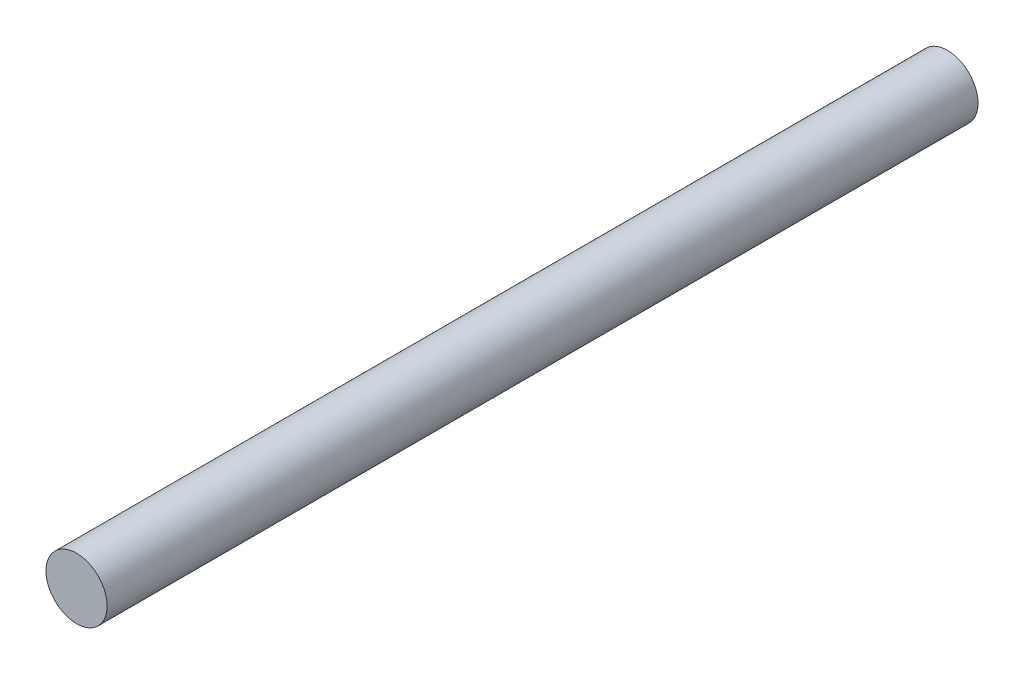
SolidWorks part; units mm, degrees
ref_plane "Front Plane" through (0, 0, 0) normal (0, 0, 1) x (1, 0, 0)
ref_plane "Top Plane" through (0, 0, 0) normal (0, 1, 0) x (1, 0, 0)
ref_plane "Right Plane" through (0, 0, 0) normal (1, 0, 0) x (0, 0, -1)
sketch "Sketch1" plane through (0, 0, 0) normal (0, 0, 1) x (1, 0, 0)
  circle A0 centre (0, 0) radius 4
  dimension "D1" = 8
extrude "Boss-Extrude1" add sketch "Sketch1" along normal blind 114
